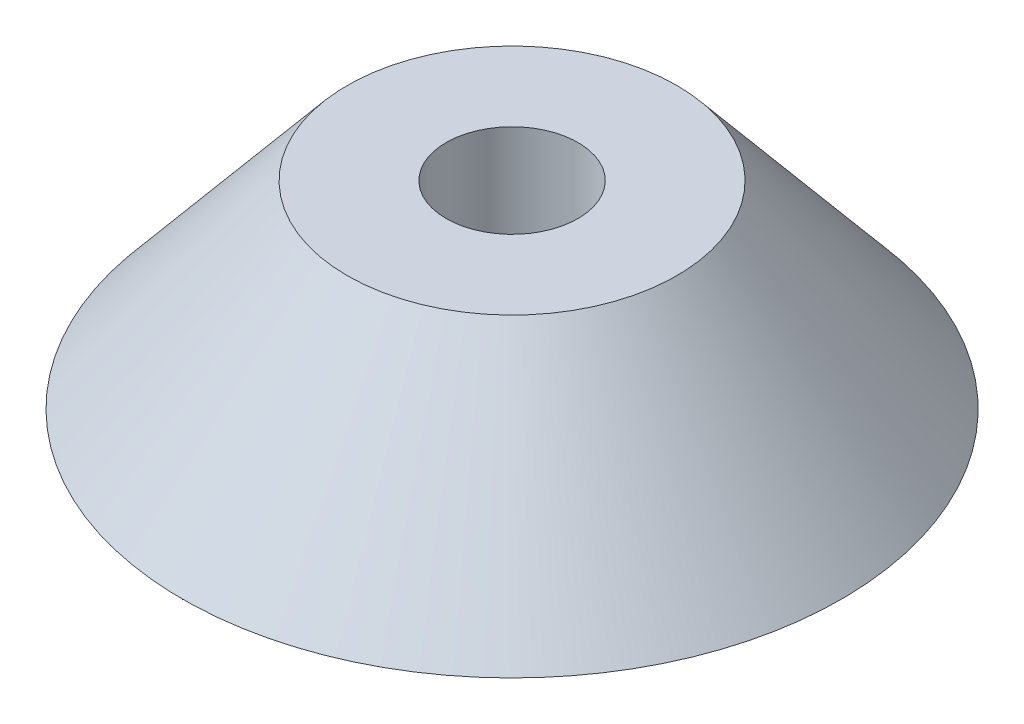
SolidWorks part; units mm, degrees
ref_plane "前视基准面" through (0, 0, 0) normal (0, 0, 1) x (1, 0, 0)
ref_plane "上视基准面" through (0, 0, 0) normal (0, 1, 0) x (1, 0, 0)
ref_plane "右视基准面" through (0, 0, 0) normal (1, 0, 0) x (0, 0, -1)
other "Configuration Table"
sketch "草图1" plane through (0, 0, 0) normal (0, 0, 1) x (1, 0, 0)
  line L0 (0, 0) -> (0, 3)
  line L1 (0, 3) -> (-2.5, 3)
  line L2 (0, 0) -> (-5, 0)
  line L3 (-2.5, 3) -> (-5, 0)
revolve "旋转1" add sketch "草图1" angle 360 about L0
sketch "草图2" plane through (0, 3, 0) normal (0, 1, 0) x (1, 0, 0)
  circle A0 centre (0, 0) radius 1
extrude "切除-拉伸1" cut sketch "草图2" against normal blind 1.8
sketch "草图3" plane through (0, 0, 0) normal (0, -1, 0) x (1, 0, 0)
  line L6 (-1.5, 0) -> (1.5, 0)
  line L7 (-1.5, 0) -> (0, 5)
  line L8 (1.5, 0) -> (0, 5)
  circle A0 centre (0, 0) radius 5 construction
extrude "凸台-拉伸1" add sketch "草图3" along normal blind 0.01 separate body
